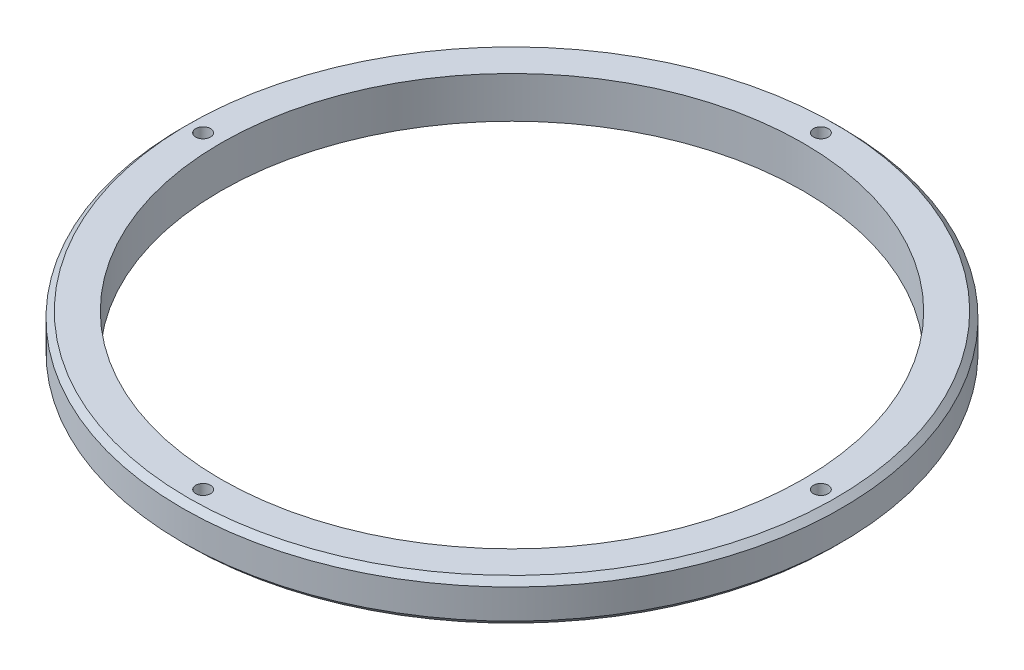
SolidWorks part; units mm, degrees
material "AISI 304"
ref_plane "Front Plane" through (0, 0, 0) normal (0, 0, 1) x (1, 0, 0)
ref_plane "Top Plane" through (0, 0, 0) normal (0, 1, 0) x (1, 0, 0)
ref_plane "Right Plane" through (0, 0, 0) normal (1, 0, 0) x (0, 0, -1)
sketch "Sketch1" plane through (0, 0, 0) normal (0, 1, 0) x (1, 0, 0)
  line L0 (0, 131.6444) -> (0, -154.3943) construction
  circle A0 centre (0, 0) radius 98.5
  circle A1 centre (0, 0) radius 111.5
  circle A2 centre (0, 0) radius 104.5 construction
  circle A3 centre (0, 104.5) radius 2.5
  circle A4 centre (104.5, 0) radius 2.5
  circle A5 centre (0, -104.5) radius 2.5
  circle A6 centre (-104.5, 0) radius 2.5
  point P18 (0, 0)
  dimension "D1" = 197
  dimension "D2" = 209
  dimension "D3" = 223
  dimension "D4" = 5
  dimension "D5" = 4
extrude "Boss-Extrude1" add sketch "Sketch1" along normal blind 14
chamfer "Chamfer1" distance 2 angle 45 2 edges at (0, 0, 111.5) (0, 14, 111.5)
